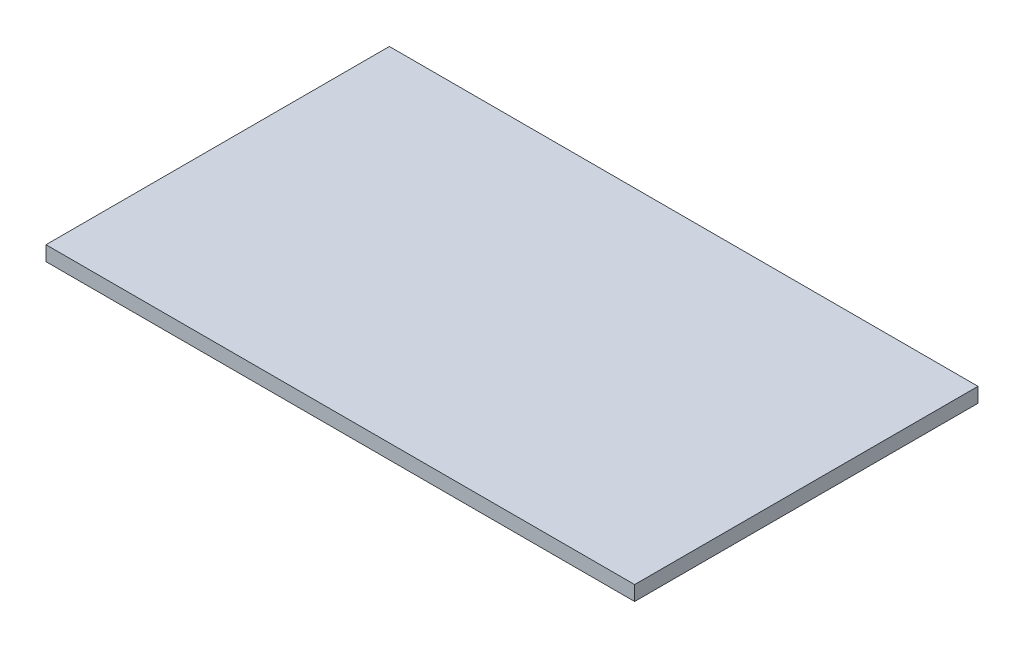
SolidWorks part; units mm, degrees
ref_plane "Front Plane" through (0, 0, 0) normal (0, 0, 1) x (1, 0, 0)
ref_plane "Top Plane" through (0, 0, 0) normal (0, 1, 0) x (1, 0, 0)
ref_plane "Right Plane" through (0, 0, 0) normal (1, 0, 0) x (0, 0, -1)
sketch "Sketch1" plane through (0, 0, 0) normal (0, 1, 0) x (1, 0, 0)
  line L1 (-30, 17.5) -> (30, 17.5)
  line L2 (-30, 17.5) -> (-30, -17.5)
  line L3 (-30, -17.5) -> (30, -17.5)
  line L4 (30, 17.5) -> (30, -17.5)
  line L5 (-30, 17.5) -> (30, -17.5) construction
  line L6 (-30, -17.5) -> (30, 17.5) construction
  point P0 (0, 0)
extrude "Boss-Extrude1" add sketch "Sketch1" along normal blind 1.5
